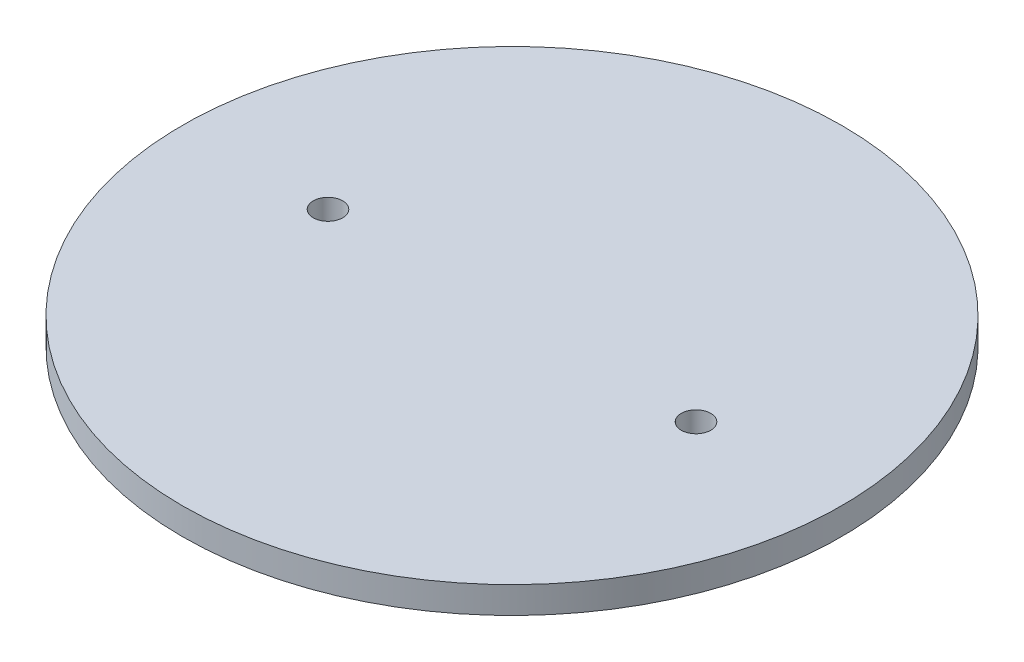
SolidWorks part; units mm, degrees
material "Balsa"
ref_plane "Front Plane" through (0, 0, 0) normal (0, 0, 1) x (1, 0, 0)
ref_plane "Top Plane" through (0, 0, 0) normal (0, 1, 0) x (1, 0, 0)
ref_plane "Right Plane" through (0, 0, 0) normal (1, 0, 0) x (0, 0, -1)
sketch "Sketch1" plane through (0, 0, 0) normal (0, 1, 0) x (1, 0, 0)
  line L0 (-49.25, 0) -> (49.25, 0) construction
  line L1 (0, 49.25) -> (0, -49.25) construction
  line L2 (49.25, 84.8597) -> (49.25, -119.3895) construction
  circle A0 centre (0, 0) radius 49.25
  circle A1 centre (-27.5, 0) radius 2.2
  circle A2 centre (27.5, 0) radius 2.2
  dimension "D1" = 55
  dimension "D2" = 4.4
extrude "Boss-Extrude1" add sketch "Sketch1" along normal blind 4
